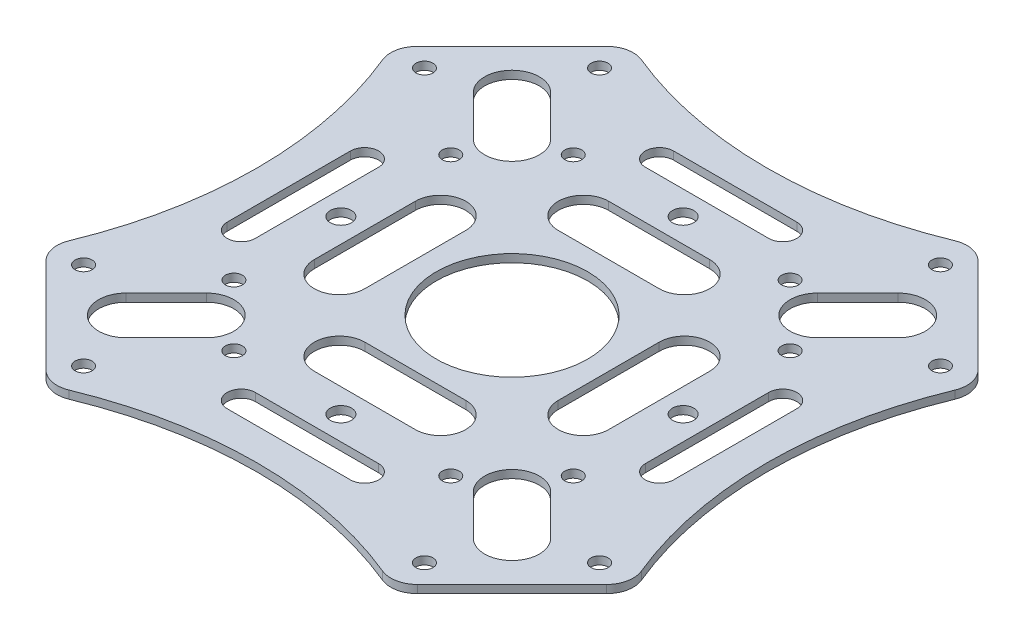
SolidWorks part; units mm, degrees
ref_plane "Front Plane" through (0, 0, 0) normal (0, 0, 1) x (1, 0, 0)
ref_plane "Top Plane" through (0, 0, 0) normal (0, 1, 0) x (1, 0, 0)
ref_plane "Right Plane" through (0, 0, 0) normal (1, 0, 0) x (0, 0, -1)
sketch "Sketch1" plane through (0, 0, 0) normal (0, 1, 0) x (1, 0, 0)
  line L0 (9.5, -27.7) -> (-9.5, -27.7)
  line L1 (-9.5, -18.2) -> (9.5, -18.2)
  line L2 (11.6, -42) -> (-11.6, -42)
  line L3 (-11.6, -36.7) -> (11.6, -36.7)
  line L4 (32.3855, -25.1023) -> (39.9515, -32.6683)
  line L5 (32.6683, -39.9515) -> (25.1023, -32.3855)
  line L6 (-9.5, 27.7) -> (9.5, 27.7)
  line L7 (9.5, 18.2) -> (-9.5, 18.2)
  line L8 (-11.6, 42) -> (11.6, 42)
  line L9 (11.6, 36.7) -> (-11.6, 36.7)
  line L10 (-32.3855, 25.1023) -> (-39.9515, 32.6683)
  line L11 (-32.6683, 39.9515) -> (-25.1023, 32.3855)
  line L12 (25.1023, 32.3855) -> (32.6683, 39.9515)
  line L13 (39.9515, 32.6683) -> (32.3855, 25.1023)
  line L14 (-34.9373, 52.7439) -> (-52.7439, 34.9373)
  line L15 (-52.7439, -34.9373) -> (-34.9373, -52.7439)
  line L16 (34.9373, -52.7439) -> (52.7439, -34.9373)
  line L17 (52.7439, 34.9373) -> (34.9373, 52.7439)
  line L18 (-25.1023, -32.3855) -> (-32.6683, -39.9515)
  line L19 (-39.9515, -32.6683) -> (-32.3855, -25.1023)
  line L20 (-42, -11.6) -> (-42, 11.6)
  line L21 (-36.7, 11.6) -> (-36.7, -11.6)
  line L22 (-27.7, -9.5) -> (-27.7, 9.5)
  line L23 (-18.2, 9.5) -> (-18.2, -9.5)
  line L24 (42, 11.6) -> (42, -11.6)
  line L25 (36.7, -11.6) -> (36.7, 11.6)
  line L26 (27.7, 9.5) -> (27.7, -9.5)
  line L27 (18.2, -9.5) -> (18.2, 9.5)
  circle A0 centre (0, 0) radius 14.25
  arc A1 (-9.5, -27.7) -> (-9.5, -18.2) centre (-9.5, -22.95) cw
  arc A2 (9.5, -18.2) -> (9.5, -27.7) centre (9.5, -22.95) cw
  arc A3 (-11.6, -42) -> (-11.6, -36.7) centre (-11.6, -39.35) cw
  arc A4 (11.6, -36.7) -> (11.6, -42) centre (11.6, -39.35) cw
  arc A5 (39.9515, -32.6683) -> (32.6683, -39.9515) centre (36.3099, -36.3099) cw
  arc A6 (25.1023, -32.3855) -> (32.3855, -25.1023) centre (28.7439, -28.7439) cw
  circle A7 centre (-32.2, 0) radius 2
  arc A8 (9.5, 27.7) -> (9.5, 18.2) centre (9.5, 22.95) cw
  arc A9 (-9.5, 18.2) -> (-9.5, 27.7) centre (-9.5, 22.95) cw
  arc A10 (11.6, 42) -> (11.6, 36.7) centre (11.6, 39.35) cw
  arc A11 (-11.6, 36.7) -> (-11.6, 42) centre (-11.6, 39.35) cw
  arc A12 (-39.9515, 32.6683) -> (-32.6683, 39.9515) centre (-36.3099, 36.3099) cw
  arc A13 (-25.1023, 32.3855) -> (-32.3855, 25.1023) centre (-28.7439, 28.7439) cw
  arc A14 (32.6683, 39.9515) -> (39.9515, 32.6683) centre (36.3099, 36.3099) cw
  arc A15 (32.3855, 25.1023) -> (25.1023, 32.3855) centre (28.7439, 28.7439) cw
  circle A16 centre (-20.4, 31.9259) radius 1.6
  circle A17 centre (-32.0673, 48.5429) radius 1.6
  circle A18 centre (-31.9259, -20.4) radius 1.6
  circle A19 centre (-48.5429, -32.0673) radius 1.6
  circle A20 centre (20.4, -31.9259) radius 1.6
  circle A21 centre (32.0673, -48.5429) radius 1.6
  circle A22 centre (31.9259, 20.4) radius 1.6
  circle A23 centre (48.5429, 32.0673) radius 1.6
  arc A24 (-52.7439, 34.9373) -> (-53.8322, 29.4991) centre (-49.2084, 31.4018) ccw
  arc A25 (-53.8322, 29.4991) -> (-53.8322, -29.4991) centre (-125.5184, 0) cw
  arc A26 (-53.8322, -29.4991) -> (-52.7439, -34.9373) centre (-49.2084, -31.4018) ccw
  arc A27 (-34.9373, -52.7439) -> (-29.4991, -53.8322) centre (-31.4018, -49.2084) ccw
  arc A28 (-29.4991, -53.8322) -> (29.4991, -53.8322) centre (0, -125.5184) cw
  arc A29 (29.4991, -53.8322) -> (34.9373, -52.7439) centre (31.4018, -49.2084) ccw
  arc A30 (52.7439, -34.9373) -> (53.8322, -29.4991) centre (49.2084, -31.4018) ccw
  arc A31 (53.8322, -29.4991) -> (53.8322, 29.4991) centre (125.5184, 0) cw
  arc A32 (53.8322, 29.4991) -> (52.7439, 34.9373) centre (49.2084, 31.4018) ccw
  arc A33 (34.9373, 52.7439) -> (29.4991, 53.8322) centre (31.4018, 49.2084) ccw
  arc A34 (29.4991, 53.8322) -> (-29.4991, 53.8322) centre (0, 125.5184) cw
  arc A35 (-29.4991, 53.8322) -> (-34.9373, 52.7439) centre (-31.4018, 49.2084) ccw
  circle A36 centre (32.0673, 48.5429) radius 1.6
  circle A37 centre (20.4, 31.9259) radius 1.6
  circle A38 centre (48.5429, -32.0673) radius 1.6
  circle A39 centre (31.9259, -20.4) radius 1.6
  circle A40 centre (-32.0673, -48.5429) radius 1.6
  circle A41 centre (-20.4, -31.9259) radius 1.6
  circle A42 centre (-48.5429, 32.0673) radius 1.6
  circle A43 centre (-31.9259, 20.4) radius 1.6
  circle A44 centre (0, 32.2) radius 2
  arc A45 (-32.6683, -39.9515) -> (-39.9515, -32.6683) centre (-36.3099, -36.3099) cw
  arc A46 (-32.3855, -25.1023) -> (-25.1023, -32.3855) centre (-28.7439, -28.7439) cw
  arc A47 (-42, 11.6) -> (-36.7, 11.6) centre (-39.35, 11.6) cw
  arc A48 (-36.7, -11.6) -> (-42, -11.6) centre (-39.35, -11.6) cw
  arc A49 (-27.7, 9.5) -> (-18.2, 9.5) centre (-22.95, 9.5) cw
  arc A50 (-18.2, -9.5) -> (-27.7, -9.5) centre (-22.95, -9.5) cw
  circle A51 centre (0, -32.2) radius 2
  arc A52 (42, -11.6) -> (36.7, -11.6) centre (39.35, -11.6) cw
  arc A53 (36.7, 11.6) -> (42, 11.6) centre (39.35, 11.6) cw
  arc A54 (27.7, -9.5) -> (18.2, -9.5) centre (22.95, -9.5) cw
  arc A55 (18.2, 9.5) -> (27.7, 9.5) centre (22.95, 9.5) cw
  circle A56 centre (32.2, 0) radius 2
extrude "Boss-Extrude1" add sketch "Sketch1" against normal mid plane 1.5
